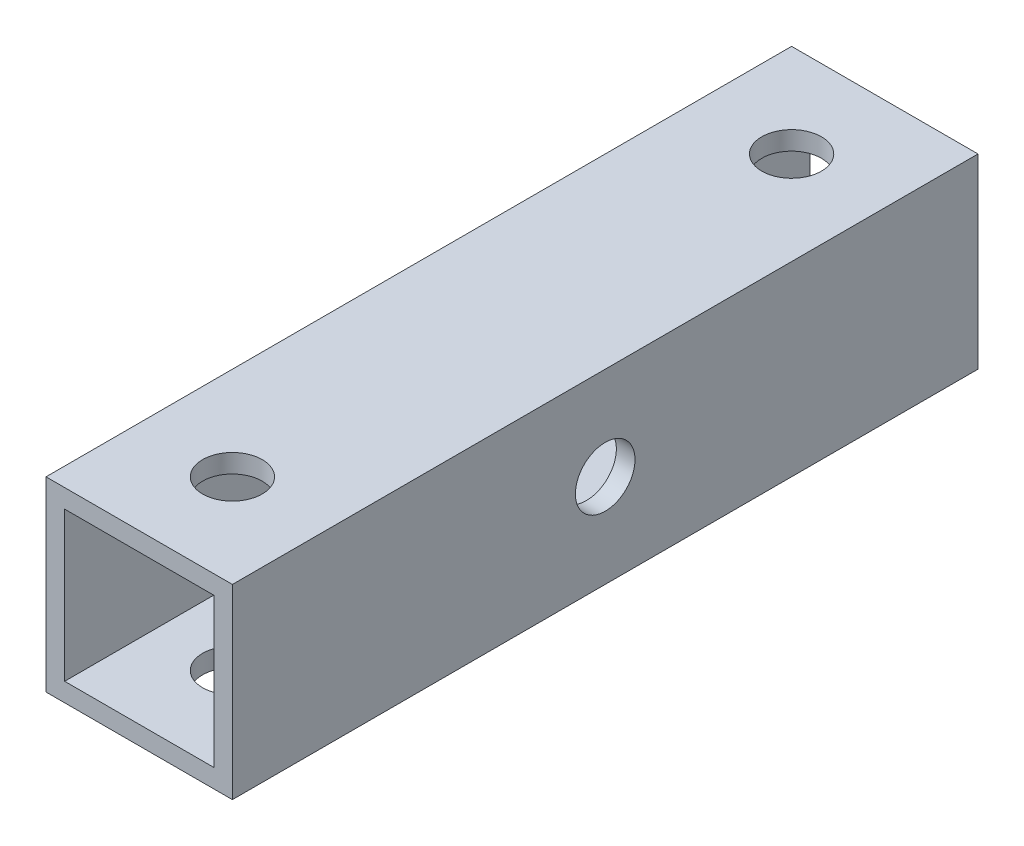
SolidWorks part; units mm, degrees
ref_plane "正面" through (0, 0, 0) normal (0, 0, 1) x (1, 0, 0)
ref_plane "平面" through (0, 0, 0) normal (0, 1, 0) x (1, 0, 0)
ref_plane "右側面" through (0, 0, 0) normal (1, 0, 0) x (0, 0, -1)
sketch "ｽｹｯﾁ1" plane through (0, 0, 0) normal (0, 0, 1) x (1, 0, 0)
  line L0 (-4, 4) -> (-4, -4)
  line L1 (-5, 5) -> (5, 5)
  line L2 (-5, 5) -> (-5, -5)
  line L3 (-5, -5) -> (5, -5)
  line L4 (5, 5) -> (5, -5)
  line L5 (-5, 5) -> (5, -5) construction
  line L6 (-5, -5) -> (5, 5) construction
  line L7 (-4, -4) -> (4, -4)
  line L8 (4, 4) -> (4, -4)
  line L9 (-4, 4) -> (4, 4)
  point P0 (0, 0)
  dimension "D1" = 10
  dimension "D2" = 10
  dimension "D3" = 1
extrude "ﾎﾞｽ - 押し出し1" add sketch "ｽｹｯﾁ1" along normal blind 40
sketch "ｽｹｯﾁ2" plane through (0, 5, 0) normal (0, 1, 0) x (1, 0, 0)
  line L0 (5, -40) -> (-5, -40) construction
  line L1 (5, 0) -> (-5, 0) construction
  circle A0 centre (0, -5) radius 1.6
  circle A1 centre (0, -35) radius 1.6
  dimension "D1" = 5
  dimension "D2" = 3.2
  dimension "D3" = 5
  dimension "D4" = 3.2
extrude "ｶｯﾄ - 押し出し1" cut sketch "ｽｹｯﾁ2" against normal blind 408.3717
sketch "ｽｹｯﾁ3" plane through (5, 0, 0) normal (1, 0, 0) x (0, 0, -1)
  line L1 (-40, -5) -> (-40, 5) construction
  circle A1 centre (-20, 0) radius 1.6
  dimension "D2" = 20
  dimension "D3" = 3.2
extrude "ｶｯﾄ - 押し出し2" cut sketch "ｽｹｯﾁ3" against normal blind 10
